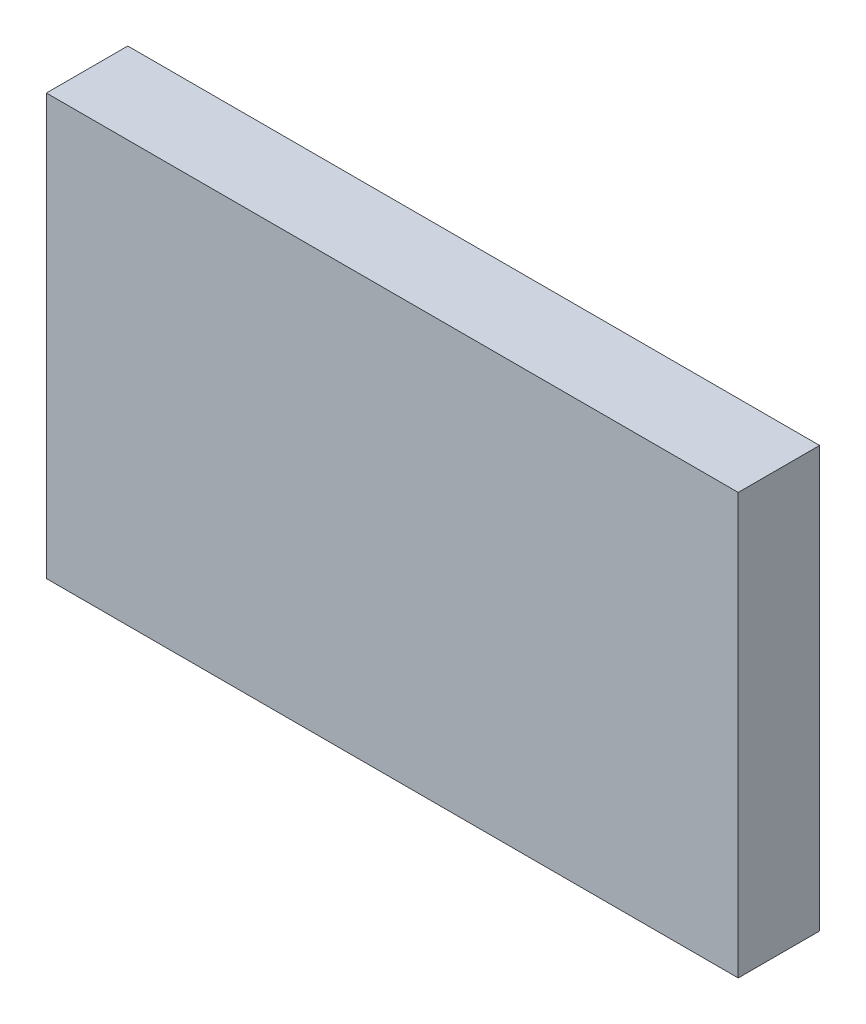
SolidWorks part; units mm, degrees
ref_plane "前视基准面" through (0, 0, 0) normal (0, 0, 1) x (1, 0, 0)
ref_plane "上视基准面" through (0, 0, 0) normal (0, 1, 0) x (1, 0, 0)
ref_plane "右视基准面" through (0, 0, 0) normal (1, 0, 0) x (0, 0, -1)
sketch "草图1" plane through (0, 0, 0) normal (0, 0, 1) x (1, 0, 0)
  line L1 (0, 0) -> (102, 0)
  line L2 (0, 0) -> (0, -62)
  line L3 (0, -62) -> (102, -62)
  line L4 (102, 0) -> (102, -62)
  dimension "D1" = 102
  dimension "D2" = 62
extrude "凸台-拉伸1" add sketch "草图1" along normal blind 12
